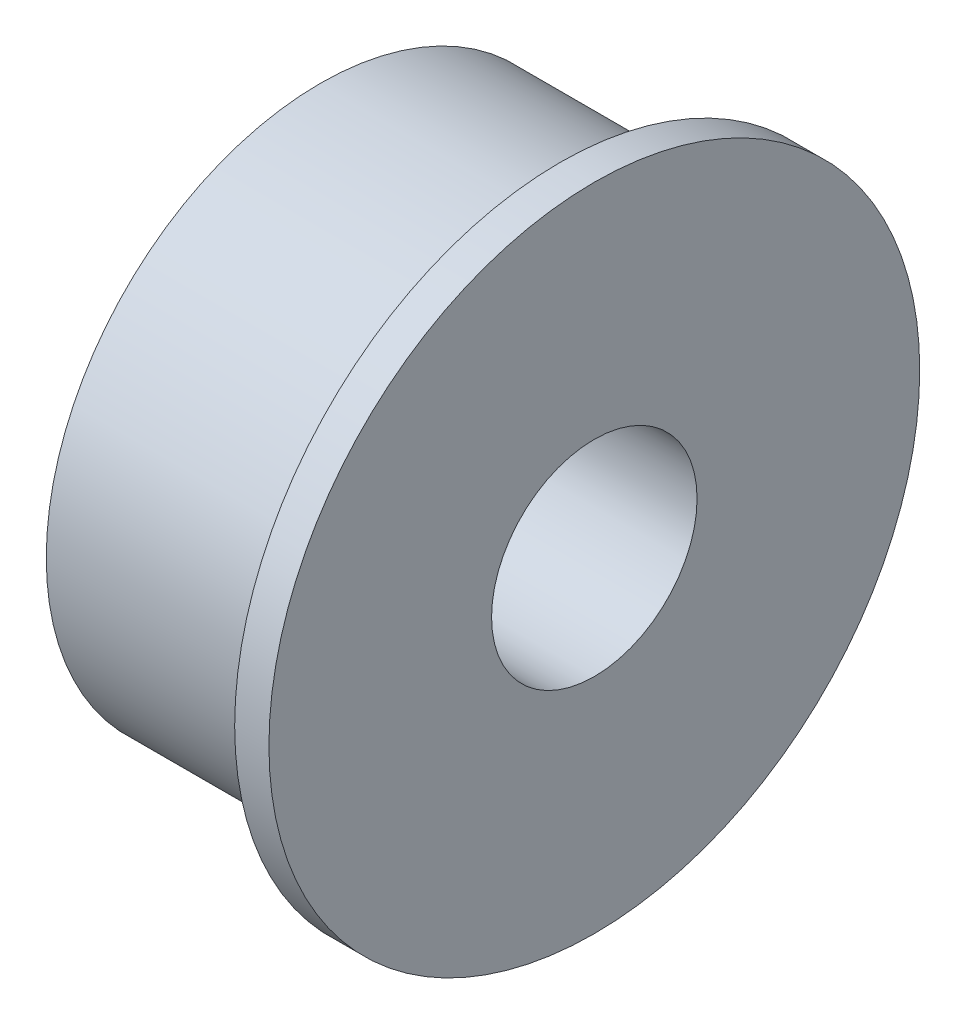
SolidWorks part; units mm, degrees
ref_plane "Front Plane" through (0, 0, 0) normal (0, 0, 1) x (1, 0, 0)
ref_plane "Top Plane" through (0, 0, 0) normal (0, 1, 0) x (1, 0, 0)
ref_plane "Right Plane" through (0, 0, 0) normal (1, 0, 0) x (0, 0, -1)
sketch "Sketch1" plane through (0, 0, 0) normal (0, 0, 1) x (1, 0, 0)
  line L0 (0, 0) -> (4.9001, 0) construction
  line L1 (0, 1.5) -> (4, 1.5)
  line L2 (4, 1.5) -> (4, 4.75)
  line L3 (4, 4.75) -> (3.5, 4.75)
  line L4 (3.5, 4.75) -> (3.5, 4)
  line L5 (3.5, 4) -> (0, 4)
  line L6 (0, 4) -> (0, 1.5)
  dimension "D1" = 4
  dimension "D2" = 4.75
  dimension "D3" = 1.5
  dimension "D4" = 4
  dimension "D5" = 0.5
revolve "Revolve1" add sketch "Sketch1" angle 360 about L0
